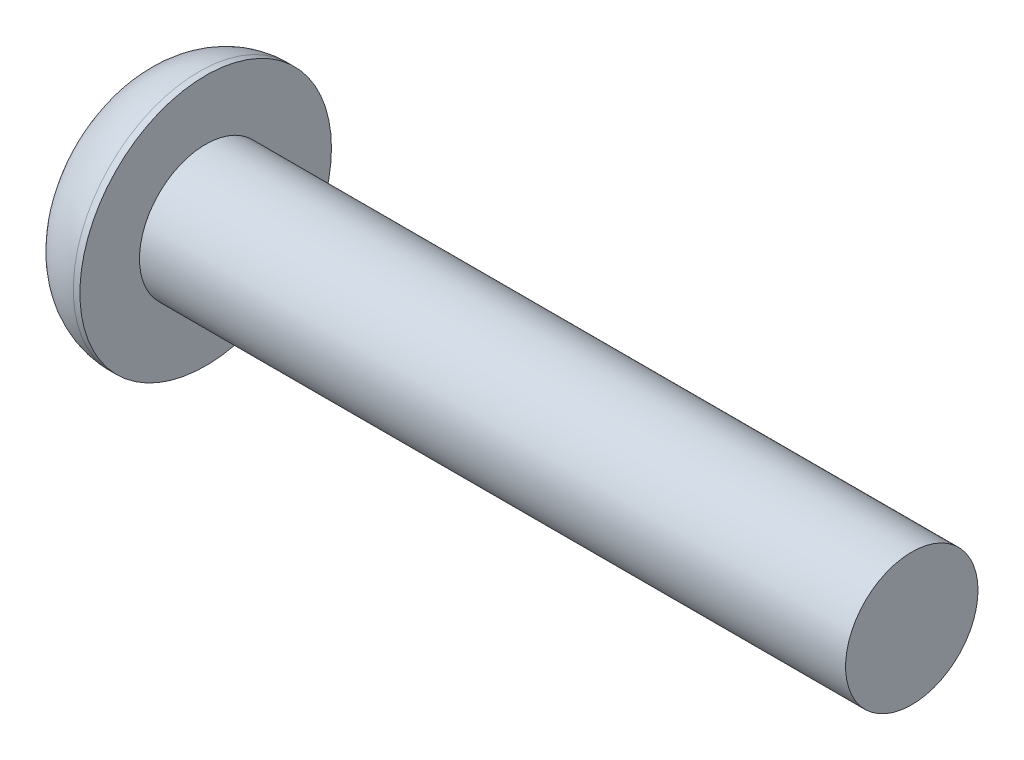
SolidWorks part; units mm, degrees
material "AISI 1020"
ref_plane "Front Plane" through (0, 0, 0) normal (0, 0, 1) x (1, 0, 0)
ref_plane "Top Plane" through (0, 0, 0) normal (0, 1, 0) x (1, 0, 0)
ref_plane "Right Plane" through (0, 0, 0) normal (1, 0, 0) x (0, 0, -1)
sketch "Sketch1" plane through (0, 0, 0) normal (0, 1, 0) x (1, 0, 0)
  line L0 (0, 0) -> (17.65, 0)
  line L1 (17.65, 0) -> (17.65, 1.5)
  line L2 (17.65, 1.5) -> (1.65, 1.5)
  line L3 (1.65, 1.5) -> (1.65, 2.85)
  line L4 (1.65, 2.85) -> (1.5, 2.85)
  line L5 (0, 1.35) -> (0, 0)
  line L6 (0, 0) -> (-8.9321, 0) construction
  arc A0 (0, 1.35) -> (1.5, 2.85) centre (1.5, 1.35) cw
  point P11 (0, 2.85)
  dimension "D5" = 1.5
  dimension "D1" = 1.5
  dimension "D2" = 16
  dimension "D3" = 1.65
  dimension "D4" = 2.85
revolve "Revolve1" add sketch "Sketch1" angle 360 about L6
sketch "Sketch2" plane through (0, 0, 0) normal (-1, 0, 0) x (0, 0, 1)
  line L1 (1.1547, 0) -> (0.5774, 1)
  line L2 (0.5774, 1) -> (-0.5774, 1)
  line L3 (-0.5774, 1) -> (-1.1547, 0)
  line L4 (-1.1547, 0) -> (-0.5774, -1)
  line L5 (-0.5774, -1) -> (0.5774, -1)
  line L6 (0.5774, -1) -> (1.1547, 0)
  circle A0 centre (0, 0) radius 1 construction
  dimension "D1" = 2
extrude "Cut-Extrude1" cut sketch "Sketch2" against normal blind 1.04
